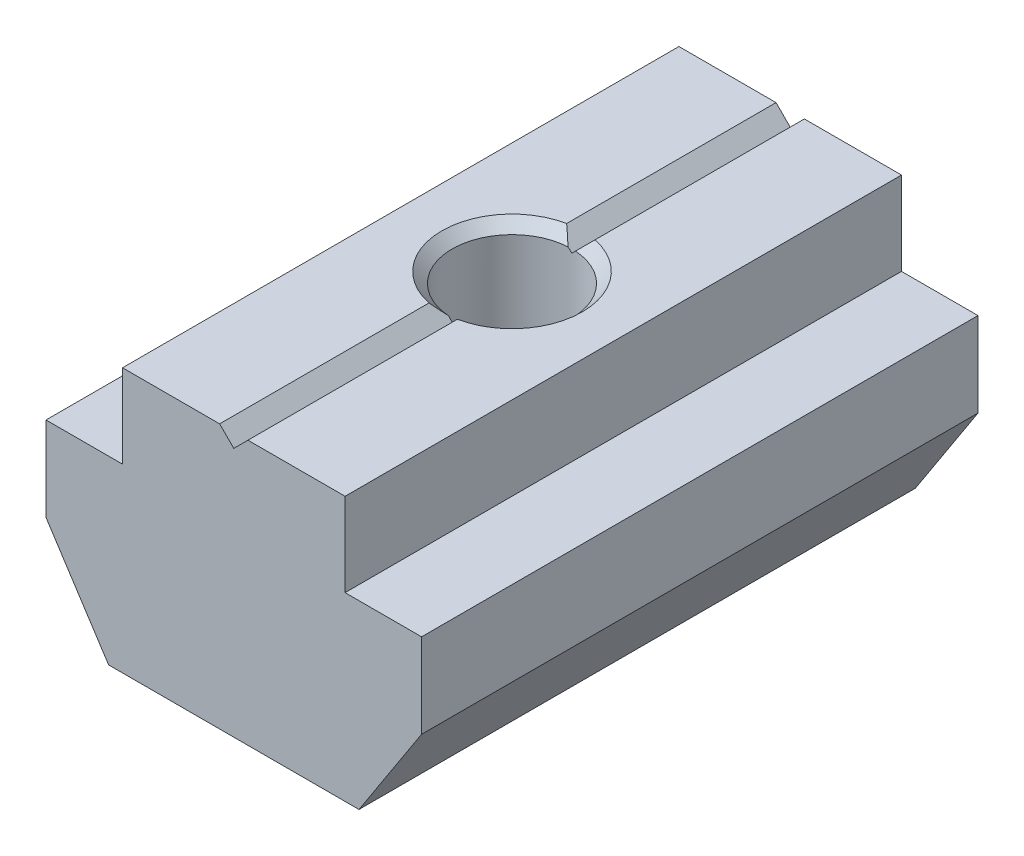
SolidWorks part; units mm, degrees
ref_plane "前视基准面" through (0, 0, 0) normal (0, 0, 1) x (1, 0, 0)
ref_plane "上视基准面" through (0, 0, 0) normal (0, 1, 0) x (1, 0, 0)
ref_plane "右视基准面" through (0, 0, 0) normal (1, 0, 0) x (0, 0, -1)
sketch "草图1" plane through (0, 0, 0) normal (0, 0, 1) x (1, 0, 0)
  line L0 (-4.5, 0) -> (4.5, 0)
  line L1 (4.5, 0) -> (6.75, 3.4647)
  line L2 (6.75, 3.4647) -> (6.75, 6.5)
  line L3 (6.75, 6.5) -> (4, 6.5)
  line L4 (4, 6.5) -> (4, 9.5)
  line L5 (4, 9.5) -> (-4, 9.5)
  line L6 (-4, 9.5) -> (-4, 6.5)
  line L7 (-4, 6.5) -> (-6.75, 6.5)
  line L8 (-6.75, 6.5) -> (-6.75, 3.4647)
  line L9 (-6.75, 3.4647) -> (-4.5, 0)
  point P0 (0, 9.5)
  dimension "D1" = 8
  dimension "D2" = 13.5
  dimension "D3" = 6.5
  dimension "D4" = 3
  dimension "D5" = 123
  dimension "D6" = 9
extrude "凸台-拉伸1" add sketch "草图1" against normal mid plane 20
sketch "草图2" plane through (0, 9.5, 0) normal (0, 1, 0) x (1, 0, 0)
  circle A0 centre (0, 0) radius 2.15
  dimension "D2" = 4.3
extrude "切除-拉伸1" cut sketch "草图2" against normal through all
cosmetic thread "装饰螺纹线1" parameters "D2"=5
sketch "草图3" plane through (0, 0, 0) normal (0, 0, 1) x (1, 0, 0)
  line L0 (-0.5091, 9.5) -> (0, 8.9909)
  line L1 (-0.5091, 9.5) -> (0, 10.0091)
  line L2 (0, 8.9909) -> (0.5091, 9.5)
  line L3 (0, 10.0091) -> (0.5091, 9.5)
  line L4 (4, 9.5) -> (-4, 9.5) construction
  dimension "D1" = 0.72
extrude "切除-拉伸2" cut sketch "草图3" against normal mid plane 20
chamfer "倒角1" distance 0.375 angle 45 3 edges at (-2.15, 0, 0) (2.15, 9.5, 0) (-2.15, 9.5, 0)
